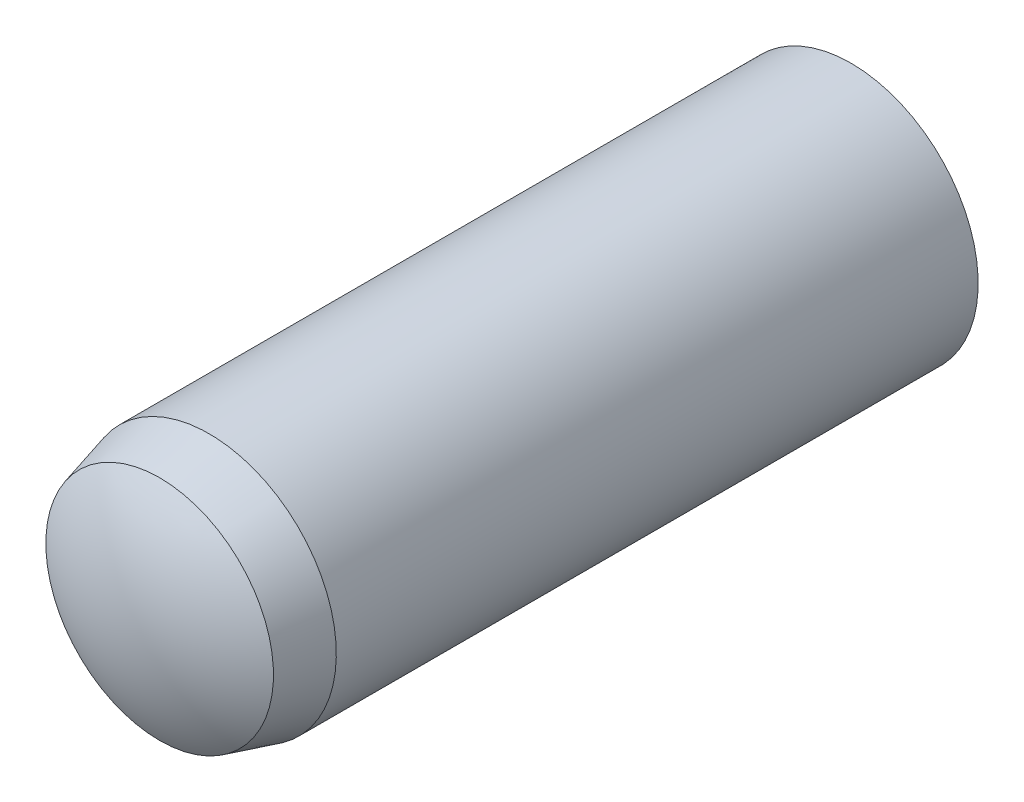
SolidWorks part; units mm, degrees
ref_plane "Front Plane" through (0, 0, 0) normal (0, 0, 1) x (1, 0, 0)
ref_plane "Top Plane" through (0, 0, 0) normal (0, 1, 0) x (1, 0, 0)
ref_plane "Right Plane" through (0, 0, 0) normal (1, 0, 0) x (0, 0, -1)
sketch "Sketch1" plane through (0, 0, 0) normal (0, 0, 1) x (1, 0, 0)
  circle A0 centre (0, 0) radius 1
  point P3 (0, 1)
  dimension "Diameter" = 2
sketch "Sketch2" plane through (0, 0, 0) normal (1, 0, 0) x (0, 0, -1)
  line L0 (-3, 0) -> (3, 0) construction
  line L1 (-3, 0) -> (-3, 1) construction
  line L2 (-3, 1) -> (3, 1)
  line L3 (3, 1) -> (3, 0) construction
  line L4 (-2.74, 0.8955) -> (-2.35, 1)
  arc A0 (-3, 0) -> (-2.74, 0.8955) centre (-1.3278, 0) cw
  arc A1 (3, 0) -> (2.7, 1) centre (1.1833, 0) ccw
  point P2 (0, 0)
  point P11 (-1, 0)
  point P13 (1, 0)
  dimension "Length" = 6
  dimension "D1" = 15
  dimension "D2" = 0.3
  dimension "D3" = 0.65
  dimension "D4" = 0.39
  dimension "D5" = 2
  dimension "D6" = 2
sketch "Sketch3" plane through (0, 0, 0) normal (1, 0, 0) x (0, 0, -1)
  line L0 (-3, 0) -> (3, 0) construction
  line L1 (-2.74, 0.8955) -> (-2.35, 1) construction
  line L2 (-3, 0) -> (3, 0)
  line L3 (-2.74, 0.8955) -> (-2.35, 1)
  line L4 (-2.35, 1) -> (2.7, 1)
  arc A0 (3, 0) -> (2.7, 1) centre (1.1833, 0) ccw construction
  arc A1 (-2.74, 0.8955) -> (-3, 0) centre (-1.3278, 0) ccw construction
  arc A2 (3, 0) -> (2.7, 1) centre (1.1833, 0) ccw
  arc A3 (-2.74, 0.8955) -> (-3, 0) centre (-1.3278, 0) ccw
revolve "Revolve1" add sketch "Sketch3" angle 360 about L2
equation "\"D2@Sketch2\" = \"Diameter@Sketch1\" * .15"
equation "\"D3@Sketch2\" = \"Diameter@Sketch1\" * .325"
equation "\"D4@Sketch2\" = \"D3@Sketch2\" * .6"
equation "\"D5@Sketch2\"=\"Diameter@Sketch1\""
equation "\"D6@Sketch2\"=\"D5@sketch2\""
